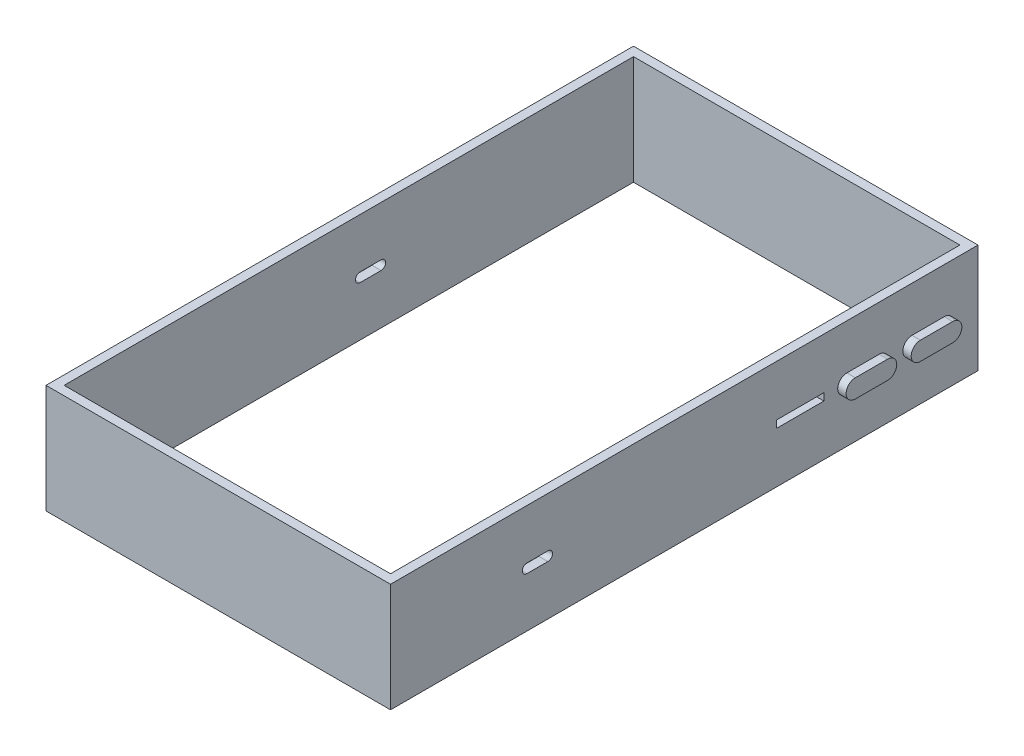
SolidWorks part; units mm, degrees
ref_plane "Front Plane" through (0, 0, 0) normal (0, 0, 1) x (1, 0, 0)
ref_plane "Top Plane" through (0, 0, 0) normal (0, 1, 0) x (1, 0, 0)
ref_plane "Right Plane" through (0, 0, 0) normal (1, 0, 0) x (0, 0, -1)
sketch "Sketch1" plane through (0, 0, 0) normal (0, 1, 0) x (1, 0, 0)
  line L1 (47.5, -81) -> (-47.5, -81)
  line L2 (47.5, -81) -> (47.5, 81)
  line L3 (47.5, 81) -> (-47.5, 81)
  line L4 (-47.5, -81) -> (-47.5, 81)
  line L5 (47.5, -81) -> (-47.5, 81) construction
  line L6 (47.5, 81) -> (-47.5, -81) construction
  point P0 (0, 0)
  dimension "D1" = 95
  dimension "D2" = 162
extrude "Boss-Extrude1" add sketch "Sketch1" along normal blind 30
sketch "Sketch2" plane through (0, 30, 0) normal (0, 1, 0) x (1, 0, 0)
  line L1 (45, -78.5) -> (-45, -78.5)
  line L2 (45, -78.5) -> (45, 78.5)
  line L3 (45, 78.5) -> (-45, 78.5)
  line L4 (-45, -78.5) -> (-45, 78.5)
  line L5 (45, -78.5) -> (-45, 78.5) construction
  line L6 (45, 78.5) -> (-45, -78.5) construction
  point P0 (0, 0)
  dimension "D1" = 90
  dimension "D2" = 157
extrude "Cut-Extrude1" cut sketch "Sketch2" against normal blind 30
sketch "Sketch3" plane through (47.5, 0, 0) normal (1, 0, 0) x (0, 0, -1)
  line L0 (71.695, 15) -> (62.805, 15) construction
  line L1 (71.695, 12.46) -> (62.805, 12.46)
  line L2 (71.695, 17.54) -> (62.805, 17.54)
  line L3 (81, 30) -> (81, 0) construction
  line L4 (53.745, 15) -> (44.855, 15) construction
  line L5 (53.745, 12.46) -> (44.855, 12.46)
  line L6 (53.745, 17.54) -> (44.855, 17.54)
  line L7 (-37.61, 15) -> (-43.39, 15) construction
  line L8 (38.5, 14) -> (25.5, 14)
  line L9 (38.5, 14) -> (38.5, 16)
  line L10 (38.5, 16) -> (25.5, 16)
  line L11 (25.5, 14) -> (25.5, 16)
  line L12 (38.5, 14) -> (25.5, 16) construction
  line L13 (38.5, 16) -> (25.5, 14) construction
  line L14 (-37.61, 13.72) -> (-43.39, 13.72)
  line L15 (-37.61, 16.28) -> (-43.39, 16.28)
  arc A0 (71.695, 12.46) -> (71.695, 17.54) centre (71.695, 15) ccw
  arc A1 (62.805, 17.54) -> (62.805, 12.46) centre (62.805, 15) ccw
  arc A2 (53.745, 12.46) -> (53.745, 17.54) centre (53.745, 15) ccw
  arc A3 (44.855, 17.54) -> (44.855, 12.46) centre (44.855, 15) ccw
  arc A4 (-37.61, 13.72) -> (-37.61, 16.28) centre (-37.61, 15) ccw
  arc A5 (-43.39, 16.28) -> (-43.39, 13.72) centre (-43.39, 15) ccw
  point P2 (67.25, 15)
  point P11 (49.3, 15)
  point P16 (32, 15)
  point P23 (-40.5, 15)
  point P28 (-44.67, 15)
  point P29 (-36.33, 15)
  dimension "D1" = 13.75
  dimension "D2" = 8.89
  dimension "D3" = 5.08
  dimension "D4" = 5.08
  dimension "D5" = 31.7
  dimension "D6" = 8.89
  dimension "D7" = 49
  dimension "D8" = 13
  dimension "D9" = 2
  dimension "D10" = 121.5
  dimension "D12" = 8.34
  dimension "D13" = 2.56
extrude "Boss-Extrude2" add sketch "Sketch3" along normal blind 2.314
sketch "Sketch4" plane through (49.814, 0, 0) normal (1, 0, 0) x (0, 0, -1)
  line L0 (25.5, 16) -> (38.5, 16)
  line L1 (38.5, 16) -> (38.5, 14)
  line L2 (38.5, 14) -> (25.5, 14)
  line L3 (25.5, 14) -> (25.5, 16)
extrude "Cut-Extrude2" cut sketch "Sketch4" against normal blind 6.632
sketch "Sketch5" plane through (49.814, 0, 0) normal (1, 0, 0) x (0, 0, -1)
  line L0 (-43.39, 16.28) -> (-37.61, 16.28)
  line L1 (-43.39, 13.72) -> (-37.61, 13.72)
  arc A0 (-37.61, 16.28) -> (-36.33, 15) centre (-37.61, 15) cw
  arc A1 (-37.61, 13.72) -> (-37.61, 16.28) centre (-37.61, 15) ccw construction
  arc A2 (-36.33, 15) -> (-37.61, 13.72) centre (-37.61, 15) cw
  arc A3 (-43.39, 16.28) -> (-44.67, 15) centre (-43.39, 15) ccw
  arc A4 (-43.39, 16.28) -> (-43.39, 13.72) centre (-43.39, 15) ccw construction
  arc A5 (-44.67, 15) -> (-43.39, 13.72) centre (-43.39, 15) ccw
extrude "Cut-Extrude3" cut sketch "Sketch5" against normal blind 6.632
sketch "Sketch6" plane through (-47.5, 0, 0) normal (-1, 0, 0) x (0, 0, 1)
  line L0 (-8.89, 15) -> (-3.11, 15) construction
  line L1 (-81, 30) -> (-81, 0) construction
  line L3 (-8.89, 16.28) -> (-3.11, 16.28)
  line L4 (-8.89, 13.72) -> (-3.11, 13.72)
  arc A0 (-8.89, 16.28) -> (-8.89, 13.72) centre (-8.89, 15) ccw
  arc A1 (-3.11, 13.72) -> (-3.11, 16.28) centre (-3.11, 15) ccw
  point P2 (0, 0)
  point P3 (0, 0)
  point P6 (-10.17, 15)
  point P7 (-1.83, 15)
  point P8 (-6, 15)
  dimension "D1" = 75
  dimension "D2" = 8.34
  dimension "D3" = 2.56
extrude "Cut-Extrude4" cut sketch "Sketch6" against normal blind 6.632
sketch "Sketch9" plane through (-47.5, 0, 0) normal (-1, 0, 0) x (0, 0, 1)
  line L0 (-81, 30) -> (-81, 0) construction
  line L2 (-59.88, 12.2576) -> (-67.5, 12.2576) construction
  line L3 (-59.88, 9.7176) -> (-67.5, 9.7176)
  line L4 (-59.88, 14.7976) -> (-67.5, 14.7976)
  arc A0 (-59.88, 9.7176) -> (-59.88, 14.7976) centre (-59.88, 12.2576) ccw
  arc A1 (-67.5, 14.7976) -> (-67.5, 9.7176) centre (-67.5, 12.2576) ccw
  point P6 (-63.69, 12.2576)
  dimension "D1" = 13.5
  dimension "D2" = 5.08
  dimension "D3" = 7.62
extrude "Boss-Extrude3" add sketch "Sketch9" along normal blind 2.54
